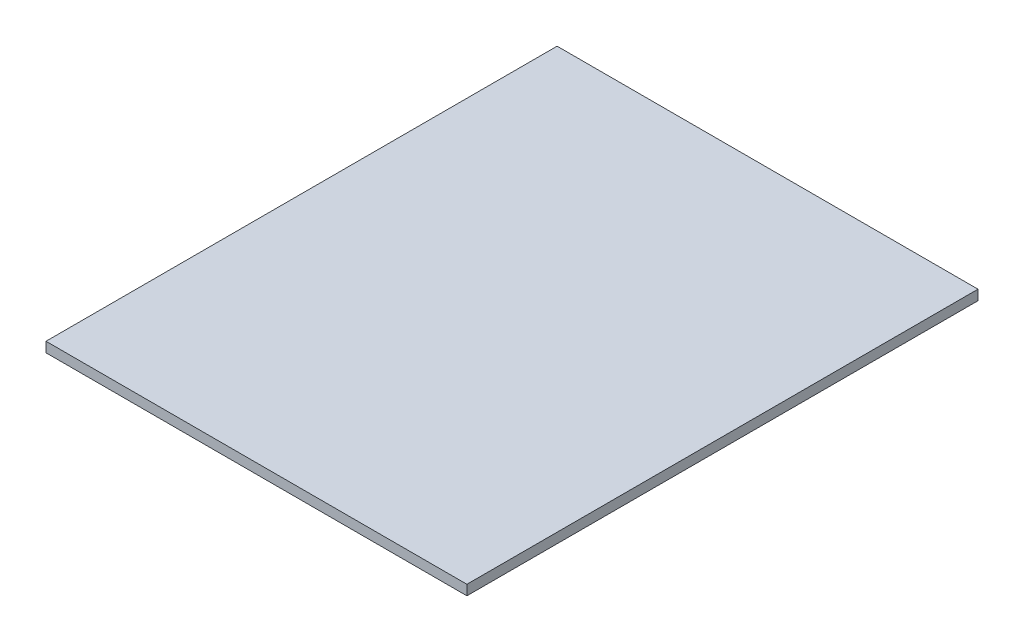
SolidWorks part; units mm, degrees
ref_plane "Front Plane" through (0, 0, 0) normal (0, 0, 1) x (1, 0, 0)
ref_plane "Top Plane" through (0, 0, 0) normal (0, 1, 0) x (1, 0, 0)
ref_plane "Right Plane" through (0, 0, 0) normal (1, 0, 0) x (0, 0, -1)
sketch "Esquisse1" plane through (0, 0, 0) normal (0, 1, 0) x (1, 0, 0)
  line L1 (-210, 255) -> (210, 255)
  line L2 (-210, 255) -> (-210, -255)
  line L3 (-210, -255) -> (210, -255)
  line L4 (210, 255) -> (210, -255)
  line L5 (-210, 255) -> (210, -255) construction
  line L6 (-210, -255) -> (210, 255) construction
  point P0 (0, 0)
extrude "Boss.-Extru.1" add sketch "Esquisse1" along normal blind 10
